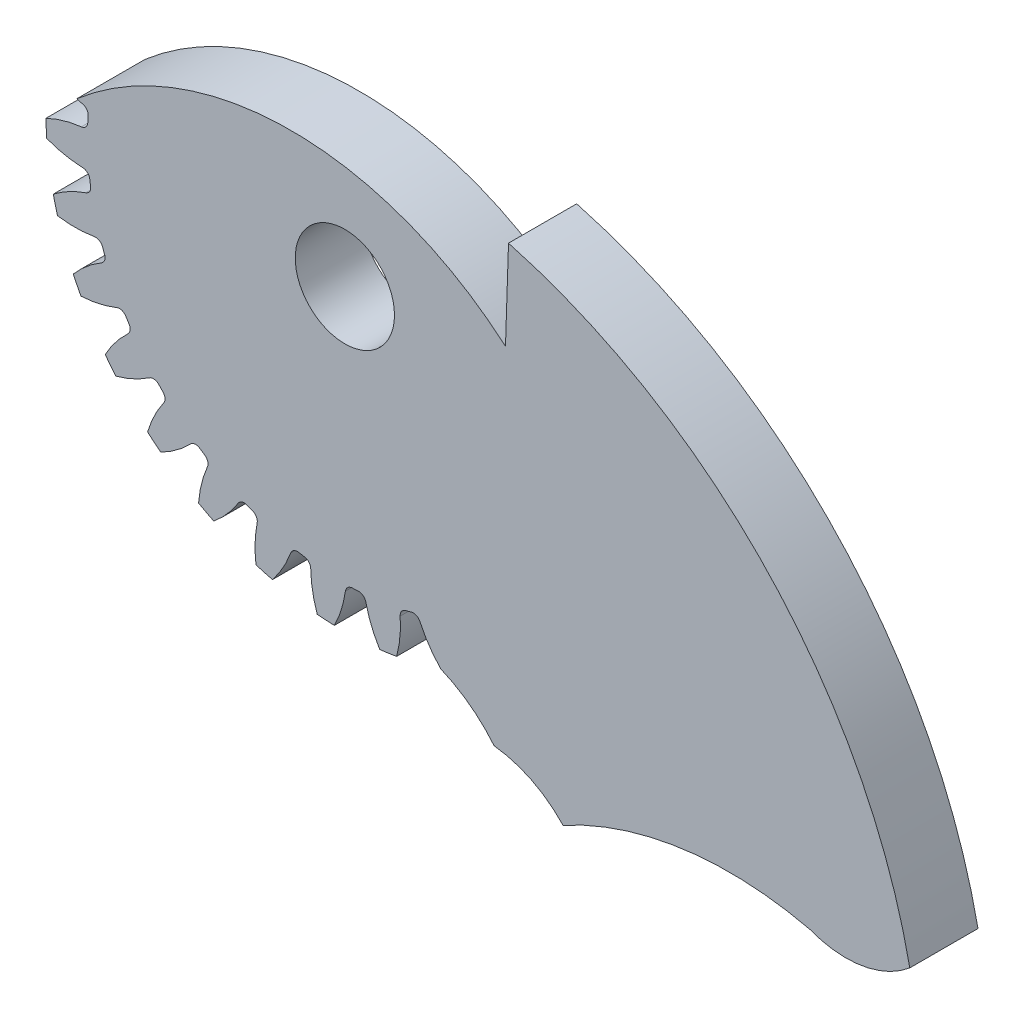
SolidWorks part; units mm, degrees
material "Delrin 2700 NC010, Low Viscosity Acetal Copolymer (SS)"
ref_plane "Front" through (0, 0, 0) normal (0, 0, 1) x (1, 0, 0)
ref_plane "Top" through (0, 0, 0) normal (0, 1, 0) x (1, 0, 0)
ref_plane "Right" through (0, 0, 0) normal (1, 0, 0) x (0, 0, -1)
sketch "Sketch3" plane through (0, 0, 0) normal (0, 0, 1) x (1, 0, 0)
  circle A0 centre (0, 0) radius 40.64
  dimension "od" = 81.28
extrude "gearBody" add sketch "Sketch3" along normal blind 25.4
sketch "Sketch2" plane through (0, 0, 0) normal (0, 0, 1) x (1, 0, 0)
  line L0 (0, 0) -> (34.0786, 14.1158) construction
  line L1 (45.4751, -11.4855) -> (0, 0) construction
  line L2 (0, 0) -> (36.3143, 0) construction
  line L3 (38.0972, -0.458) -> (37.8451, -4.4001) construction
  line L5 (37.9712, -2.4291) -> (0, 0) construction
  line L7 (0, 0) -> (36.8864, 0) construction
  arc A0 (36.879, -0.7403) -> (36.6727, -3.9649) centre (0, 0) ccw construction
  arc A1 (40.637, 0.4947) -> (40.2427, -5.6687) centre (0, 0) ccw construction
  arc A2 (38.0972, -0.458) -> (37.8451, -4.4001) centre (0, 0) ccw construction
  arc A3 (34.9015, -2.6404) -> (34.9534, -1.8283) centre (0, 0) ccw
  arc A4 (45.4751, -11.4855) -> (35.6466, -3.6712) centre (32.0022, -18.3431) ccw
  arc A5 (45.4751, -11.4855) -> (46.5679, 5.5974) centre (0, 0) ccw
  arc A6 (46.5679, 5.5974) -> (35.8238, -0.9008) centre (34.0786, 14.1158) cw
  arc A7 (34.9534, -1.8283) -> (35.8238, -0.9008) centre (35.9376, -1.8798) cw
  arc A8 (35.6466, -3.6712) -> (34.9015, -2.6404) centre (35.8842, -2.7147) cw
  point P6 (46.5679, 5.5974)
  point P22 (45.4751, -11.4855)
  dimension "baseDia" = 73.7729
  dimension "od" = 81.28
  dimension "pd" = 76.2
  dimension "rd" = 70.0024
  dimension "rFillet" = 0.9855
  dimension "pointX" = 46.5679
  dimension "pointY" = 5.5974
  dimension "CTT" = 3.9421
  dimension "flankCenterAngle" = 22.5
extrude "toothCut" cut sketch "Sketch2" along normal through all
pattern_circular "CirPattern1" count 30 over 360 about axis through (0, 0, 0) along (0, 0, 1) of "toothCut"
sketch "hub1Dia" plane through (0, 0, 0) normal (0, 0, -1) x (-1, 0, 0)
  circle A0 centre (0, 0) radius 12.7
  dimension "hub1Dia" = 25.4
sketch "hub2Dia" plane through (0, 0, 25.4) normal (0, 0, 1) x (1, 0, 0)
  circle A0 centre (0, 0) radius 12.7
  dimension "hub2dia" = 25.4
sketch "boreDia" plane through (0, 0, 0) normal (0, 0, 1) x (1, 0, 0)
  circle A0 centre (0, 0) radius 9.525
  dimension "boreDia" = 19.05
extrude "bore" cut sketch "boreDia" against normal mid plane 25400
sketch "Sketch4" plane through (0, 0, 25.4) normal (0, 0, 1) x (1, 0, 0)
  circle A0 centre (1.8913, -57.4779) radius 76.1746
  arc A1 (46.3822, 4.3535) -> (-43.5544, 3.6553) centre (1.4277, 2.2323) ccw
  dimension "D1" = 152.3492
extrude "Cut-Extrude1" cut sketch "Sketch4" against normal through all contours A0 A1
sketch "Sketch5" plane through (0, 0, 25.4) normal (0, 0, 1) x (1, 0, 0)
  line L0 (-40.5204, 5.7978) -> (17.7171, 12.4887)
  line L1 (17.7171, 12.4887) -> (8.9608, -26.928)
  line L2 (8.9608, -26.928) -> (13.028, -38.4952)
  arc A2 (13.028, -38.4952) -> (24.1586, -52.1288) centre (5.7938, -55.7616) cw
  arc A3 (63.24, -44.0814) -> (24.1586, -52.1288) centre (52.353, -90.1309) ccw
  arc A7 (76.8188, -41.8196) -> (-40.5204, 5.7978) centre (2.2241, -57.2535) ccw
  arc A8 (63.24, -44.0814) -> (76.8188, -41.8196) centre (68.1274, -31.5314) ccw
  arc A9 (32.8322, 12.1298) -> (-33.5657, 9.9415) centre (1.8913, -57.4779) ccw construction
  dimension "D2" = 152.3492
extrude "Boss-Extrude1" add sketch "Sketch5" against normal up to surface (25.4 mm away) up to face at (9.525, 0, 0)
sketch "Sketch6" plane through (0, 0, 0) normal (0, 1, 0) x (1, 0, 0)
  line L0 (-46.1384, -9.271) -> (97.8162, -9.271)
  line L4 (97.8162, -9.271) -> (71.9328, -41.1538)
  line L5 (71.9328, -41.1538) -> (-48.6783, -38.0647)
  line L6 (-48.6783, -38.0647) -> (-46.1384, -9.271)
  dimension "D1" = 9.271
extrude "Cut-Extrude2" cut sketch "Sketch6" against normal through all both and the other way through all
sketch "Sketch7" plane through (0, 0, 9.271) normal (0, 0, 1) x (1, 0, 0)
  line L0 (21.8411, 3.894) -> (22.2513, 16.2413)
  line L1 (-36.4485, 3.894) -> (-43.5776, 3.303)
  line L2 (-43.5776, 3.303) -> (-36.8766, 21.2616)
  line L3 (-36.8766, 21.2616) -> (23.9011, 23.2048)
  line L4 (23.9011, 23.2048) -> (22.2513, 16.2413)
  arc A0 (-40.2427, 5.6687) -> (-35.6466, 3.6712) centre (-32.0022, 18.3431) ccw construction
  arc A1 (76.8188, -41.8196) -> (-40.5204, 5.7978) centre (2.2241, -57.2535) ccw construction
  arc A2 (-36.4485, 3.894) -> (21.8411, 3.894) centre (-7.3037, -29.8805) cw
  point P0 (-36.4485, 3.894)
  point P1 (-5.3442, 14.9882)
  point P5 (21.8411, 3.894)
  point P6 (21.4449, 16.4563)
  point P7 (21.8411, 14.3516)
  point P11 (22.2513, 12.4032)
  point P12 (22.2513, 10.6257)
  point P13 (21.8411, 9.0875)
  point P14 (21.8411, 7.4467)
  point P15 (21.8411, 5.8743)
extrude "Cut-Extrude3" cut sketch "Sketch7" against normal through all both
sketch "Sketch8" plane through (0, 0, 9.271) normal (0, 0, 1) x (1, 0, 0)
  circle A0 centre (0, 0) radius 6.7469
  circle A1 centre (0, 0) radius 10.9012
  dimension "D1" = 13.4937
extrude "Boss-Extrude2" add sketch "Sketch8" against normal up to surface (9.271 mm away) up to face at (-14.6896, -23.323, 0)
sketch "Sketch9" plane through (0, 0, 9.271) normal (0, 0, 1) x (1, 0, 0)
  line L0 (20.2954, -43.9224) -> (23.1683, -52.6945)
  line L1 (23.1683, -52.6945) -> (26.5794, -52.804)
  line L2 (26.5794, -52.804) -> (29.6611, -48.6079)
  arc A0 (24.1586, -52.1288) -> (13.028, -38.4952) centre (5.7938, -55.7616) ccw construction
  arc A1 (63.24, -44.0814) -> (24.1586, -52.1288) centre (52.353, -90.1309) ccw construction
  arc A2 (20.2954, -43.9224) -> (29.6611, -48.6079) centre (18.6746, -58.8652) cw
  point P0 (27.8575, -49.0551)
  point P1 (25.2947, -45.6047)
  point P2 (22.4218, -43.2707)
  point P3 (19.1914, -41.3058)
  point P4 (20.2954, -43.9224)
  point P5 (29.6611, -48.6079)
extrude "Cut-Extrude4" cut sketch "Sketch9" against normal through all both
